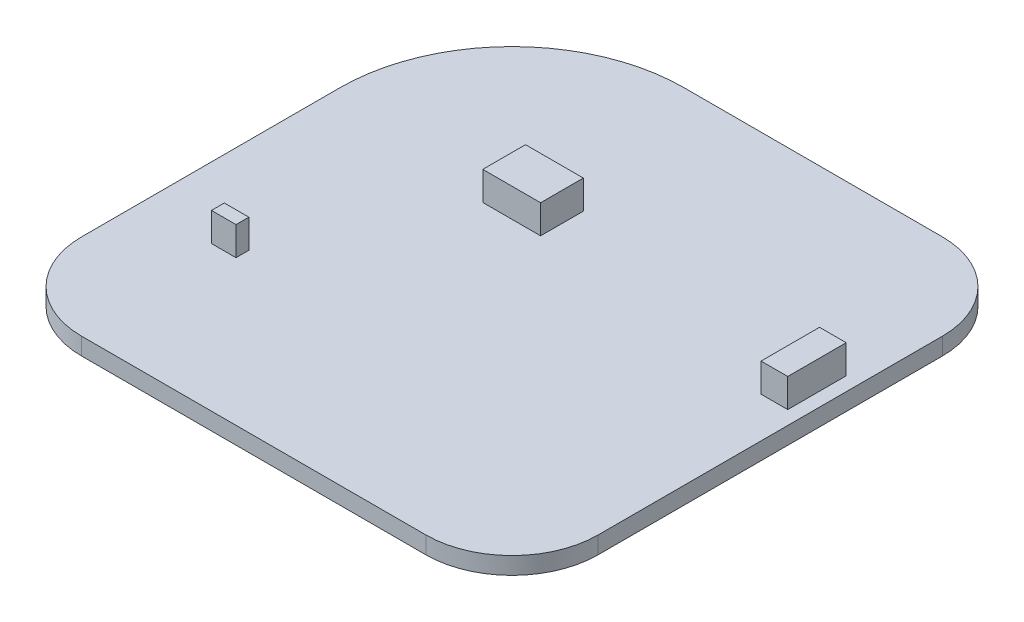
SolidWorks part; units mm, degrees
ref_plane "Front Plane" through (0, 0, 0) normal (0, 0, 1) x (1, 0, 0)
ref_plane "Top Plane" through (0, 0, 0) normal (0, 1, 0) x (1, 0, 0)
ref_plane "Right Plane" through (0, 0, 0) normal (1, 0, 0) x (0, 0, -1)
sketch "Sketch2" plane through (0, 0, 0) normal (0, 1, 0) x (1, 0, 0)
  line L1 (-10, 30) -> (20, 30)
  line L2 (-30, 10) -> (-30, -20)
  line L3 (-20, -30) -> (20, -30)
  line L4 (30, 20) -> (30, -20)
  line L5 (-30, 30) -> (30, -30) construction
  line L6 (-30, -30) -> (30, 30) construction
  arc A0 (-10, 30) -> (-30, 10) centre (-10, 10) ccw
  arc A1 (-30, -20) -> (-20, -30) centre (-20, -20) ccw
  arc A2 (20, -30) -> (30, -20) centre (20, -20) ccw
  arc A3 (20, 30) -> (30, 20) centre (20, 20) cw
  point P0 (0, 0)
  dimension "D3" = 20
  dimension "D4" = 10
  dimension "D1" = 60
  dimension "D2" = 60
extrude "Boss-Extrude1" add sketch "Sketch2" along normal blind 2
scale "Scale1" scale about centroid uniform scaling yes scale factor 0.9
sketch "Sketch3" plane through (0, 1.9, 0) normal (0, 1, 0) x (1, 0, 0)
  line L1 (-3.0453, 10.5049) -> (-9.0921, 10.5049)
  line L2 (-3.0453, 10.5049) -> (-3.0453, 6.0361)
  line L3 (-3.0453, 6.0361) -> (-9.0921, 6.0361)
  line L4 (-9.0921, 10.5049) -> (-9.0921, 6.0361)
  line L5 (-3.0453, 10.5049) -> (-9.0921, 6.0361) construction
  line L6 (-3.0453, 6.0361) -> (-9.0921, 10.5049) construction
  point P4 (-6.0687, 8.2705)
extrude "Boss-Extrude2" add sketch "Sketch3" along normal blind 3
sketch "Sketch4" plane through (0, 1.9, 0) normal (0, 1, 0) x (1, 0, 0)
  line L1 (25.6075, 9.339) -> (22.8171, 9.339)
  line L2 (25.6075, 9.339) -> (25.6075, 3.2236)
  line L3 (25.6075, 3.2236) -> (22.8171, 3.2236)
  line L4 (22.8171, 9.339) -> (22.8171, 3.2236)
  line L5 (25.6075, 9.339) -> (22.8171, 3.2236) construction
  line L6 (25.6075, 3.2236) -> (22.8171, 9.339) construction
  point P4 (24.2123, 6.2813)
extrude "Boss-Extrude3" add sketch "Sketch4" along normal blind 3
sketch "Sketch5" plane through (0, 1.9, 0) normal (0, 1, 0) x (1, 0, 0)
  line L1 (-19.5588, -10.5237) -> (-16.9927, -10.5237)
  line L2 (-19.5588, -10.5237) -> (-19.5588, -11.8699)
  line L3 (-19.5588, -11.8699) -> (-16.9927, -11.8699)
  line L4 (-16.9927, -10.5237) -> (-16.9927, -11.8699)
  line L5 (-19.5588, -10.5237) -> (-16.9927, -11.8699) construction
  line L6 (-19.5588, -11.8699) -> (-16.9927, -10.5237) construction
  point P4 (-18.2757, -11.1968)
extrude "Boss-Extrude4" add sketch "Sketch5" along normal blind 3
